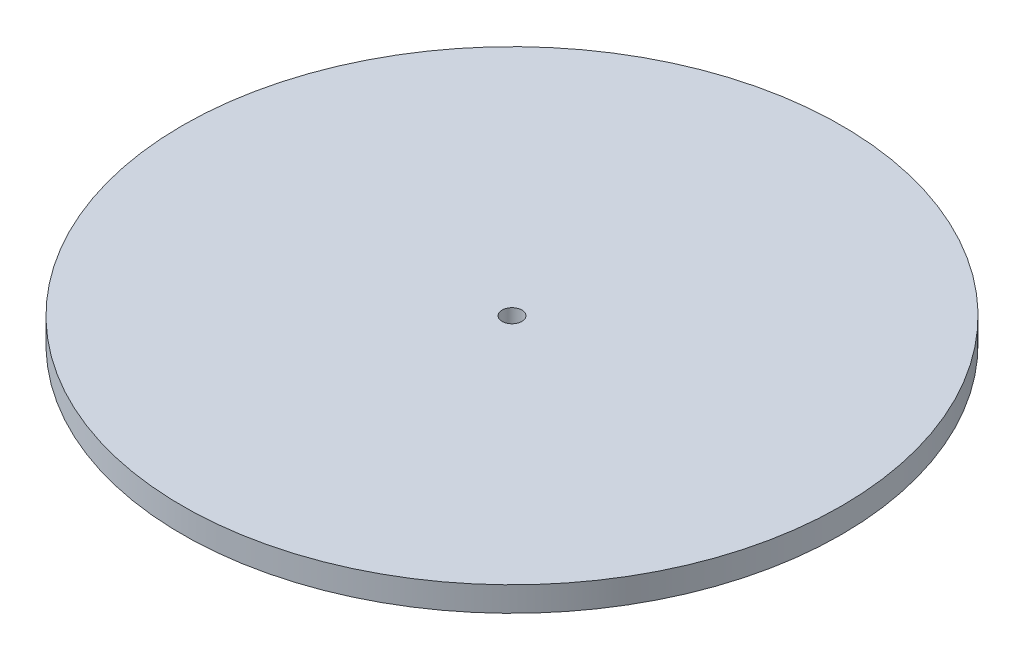
SolidWorks part; units mm, degrees
ref_plane "Front Plane" through (0, 0, 0) normal (0, 0, 1) x (1, 0, 0)
ref_plane "Top Plane" through (0, 0, 0) normal (0, 1, 0) x (1, 0, 0)
ref_plane "Right Plane" through (0, 0, 0) normal (1, 0, 0) x (0, 0, -1)
sketch "Sketch3" plane through (0, 0, 0) normal (0, 0, 1) x (1, 0, 0)
  line L0 (37, 6.6124) -> (37, 10.6124) construction
  line L1 (37, 10.6124) -> (0, 10.6124) construction
  line L2 (0, 10.6124) -> (0, 0) construction
  line L4 (1.2, 10.6124) -> (1.2, 5.6124)
  line L5 (1.2, 5.6124) -> (0, 5.6124)
  line L6 (0, 5.6124) -> (0, 0)
  line L7 (37, 6.6124) -> (40, 6.6124) construction
  line L8 (40, 6.6124) -> (40, 10.6124) construction
  line L9 (40, 10.6124) -> (1.2, 10.6124)
  line L10 (37, 6.6124) -> (37, 7.6124)
  line L11 (37, 7.6124) -> (40, 7.6124)
  line L12 (40, 7.6124) -> (40, 10.6124)
  spline S0 degree 8 poles (-3.7, 0.1038) (1.8446, -0.1995) (7.3892, -0.0399) (12.9337, 0.9279) (18.4783, 2.1357) (24.0229, 3.4181) (29.5675, 4.7948) (35.1121, 6.1479) (40.6567, 7.5092) knots 0 0 0 0 0 0 0 0 0 1 1 1 1 1 1 1 1 1 construction
  spline S1 degree 8 poles (0, 0) (4.625, 0.0008) (9.25, 0.3875) (13.875, 1.1876) (18.5, 2.1694) (23.125, 3.2308) (27.75, 4.3493) (32.375, 5.4792) (37, 6.6124) knots 0.083415 0.083415 0.083415 0.083415 0.083415 0.083415 0.083415 0.083415 0.083415 0.917562 0.917562 0.917562 0.917562 0.917562 0.917562 0.917562 0.917562 0.917562
  dimension "D1" = 3
  dimension "D2" = 1.2
  dimension "D3" = 5
  dimension "D4" = 3
  dimension "D5" = 40
  dimension "D6" = 6.6124
  dimension "D7" = 37
  dimension "D8" = 4
revolve "Revolve4" add sketch "Sketch3" angle 360 about L2
sketch "Sketch5" plane through (0, 10.6124, 0) normal (0, 1, 0) x (1, 0, 0)
  circle A0 centre (0, 0) radius 1.2
  circle A2 centre (0, 0) radius 1.2 construction
extrude "Cut-Extrude1" cut sketch "Sketch5" against normal through all
